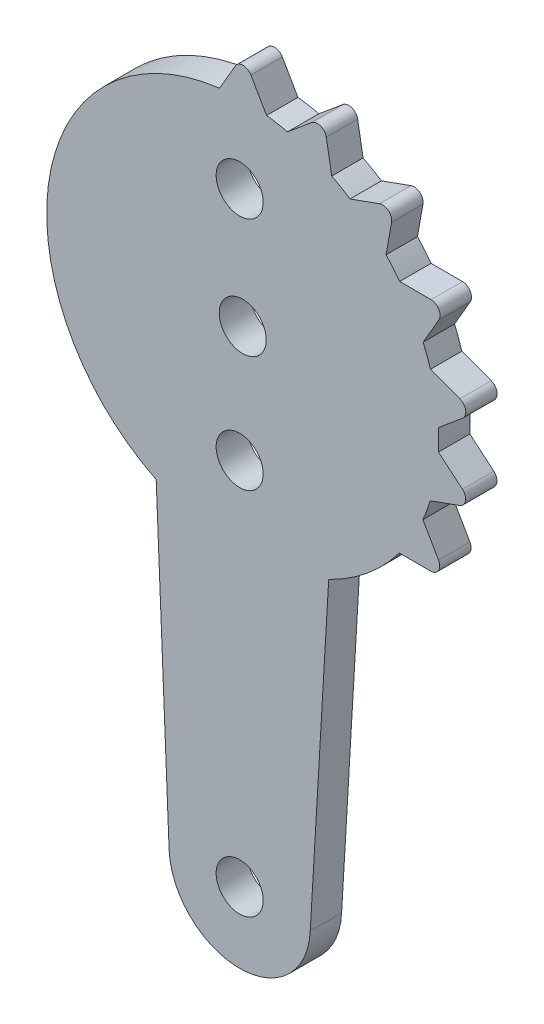
SolidWorks part; units mm, degrees
ref_plane "Front Plane" through (0, 0, 0) normal (0, 0, 1) x (1, 0, 0)
ref_plane "Top Plane" through (0, 0, 0) normal (0, 1, 0) x (1, 0, 0)
ref_plane "Right Plane" through (0, 0, 0) normal (1, 0, 0) x (0, 0, -1)
sketch "Sketch1" plane through (0, 0, 0) normal (0, 0, 1) x (1, 0, 0)
  line L0 (-5.3228, 19.8328) -> (-4.5, -0.185)
  line L1 (5.6772, 19.8147) -> (4.5, -0.1853)
  line L2 (4.5859, 44.5001) -> (3.0506, 43.2183)
  line L3 (0.7204, 45.1904) -> (1.7162, 43.4559)
  line L4 (-0.2796, 45.1904) -> (-1.2838, 43.4608)
  line L5 (5.5255, 44.158) -> (5.868, 42.1876)
  line L6 (8.9217, 42.1873) -> (7.0407, 41.5079)
  line L7 (9.6878, 41.5445) -> (9.3356, 39.5758)
  line L8 (12.2051, 38.5311) -> (10.2051, 38.536)
  line L9 (12.7051, 37.665) -> (11.7008, 35.9355)
  line L10 (14.04, 33.9723) -> (12.1623, 34.661)
  line L11 (14.2136, 32.9875) -> (12.6784, 31.7058)
  line L12 (14.205, 29.061) -> (12.6761, 30.3504)
  line L13 (14.0314, 28.0762) -> (12.1503, 27.3968)
  line L14 (12.6803, 24.3894) -> (11.6846, 26.1239)
  line L15 (12.1803, 23.5233) -> (10.1803, 23.5283)
  arc A0 (-5.3228, 19.8328) -> (-1.2838, 43.4608) centre (0.1956, 31.0487) cw
  arc A1 (-4.5, -0.185) -> (4.5, -0.1853) centre (0, 0) ccw
  circle A2 centre (0.1956, 31.0487) radius 1.5
  circle A3 centre (0, 38.5461) radius 1.5
  circle A4 centre (0, 23.5512) radius 1.5
  circle A5 centre (0, 0) radius 1.5
  arc A6 (-0.2796, 45.1904) -> (0.7204, 45.1904) centre (0.2204, 44.9001) cw
  arc A7 (1.7162, 43.4559) -> (3.0506, 43.2183) centre (0.1956, 31.0487) cw
  arc A8 (4.5859, 44.5001) -> (5.5255, 44.158) centre (4.9564, 44.0562) cw
  arc A9 (8.9217, 42.1873) -> (9.6878, 41.5445) centre (9.1181, 41.6435) cw
  arc A10 (12.2051, 38.5311) -> (12.7051, 37.665) centre (12.2037, 37.9529) cw
  arc A11 (14.04, 33.9723) -> (14.2136, 32.9875) centre (13.8409, 33.4295) cw
  arc A12 (14.205, 29.061) -> (14.0314, 28.0762) centre (13.8323, 28.619) cw
  arc A13 (12.6803, 24.3894) -> (12.1803, 23.5233) centre (12.1789, 24.1015) cw
  arc A14 (9.3356, 39.5758) -> (10.2051, 38.536) centre (0.1956, 31.0487) cw
  arc A15 (5.868, 42.1876) -> (7.0407, 41.5079) centre (0.1956, 31.0487) cw
  arc A16 (11.7008, 35.9355) -> (12.1623, 34.661) centre (0.1956, 31.0487) cw
  arc A17 (12.6784, 31.7058) -> (12.6761, 30.3504) centre (0.1956, 31.0487) cw
  arc A18 (12.1503, 27.3968) -> (11.6846, 26.1239) centre (0.1956, 31.0487) cw
  arc A19 (10.1803, 23.5283) -> (5.6772, 19.8147) centre (0.1956, 31.0487) cw
  point P50 (0.1956, 31.0487)
  dimension "D1" = 3
  dimension "D2" = 3
  dimension "D3" = 12.5
  dimension "D6" = 9
  dimension "D8" = 4.5038
  dimension "D11" = 3
  dimension "D4" = 7.5
  dimension "D5" = 7.5
  dimension "D7" = 11
  dimension "D9" = 20
  dimension "D10" = 31.0487
  dimension "D12" = 44.9001
  dimension "D13" = 7
  dimension "D14" = 2
  dimension "D15" = 2
  dimension "D16" = 1
extrude "Boss-Extrude1" add sketch "Sketch1" along normal blind 2
